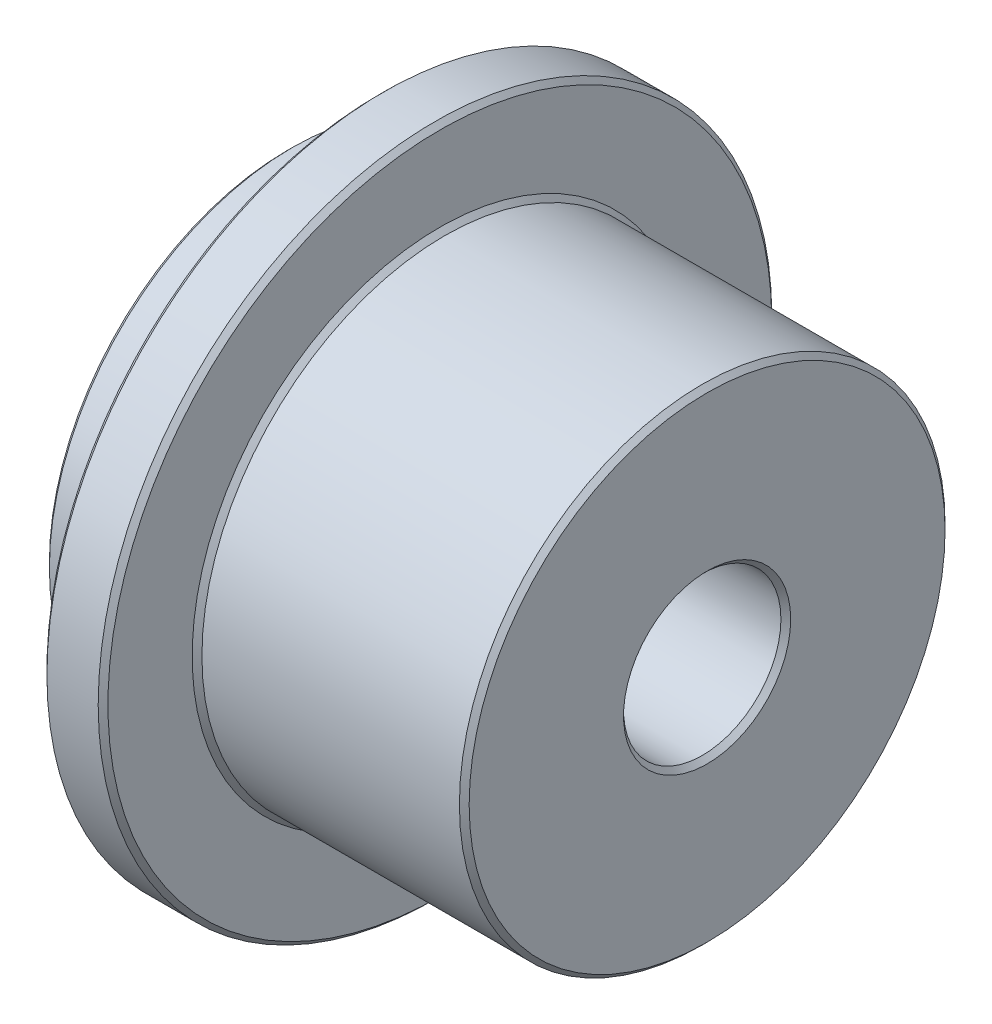
SolidWorks part; units mm, degrees
ref_plane "Front Plane" through (0, 0, 0) normal (0, 0, 1) x (1, 0, 0)
ref_plane "Top Plane" through (0, 0, 0) normal (0, 1, 0) x (1, 0, 0)
ref_plane "Right Plane" through (0, 0, 0) normal (1, 0, 0) x (0, 0, -1)
sketch "Sketch1" plane through (0, 0, 0) normal (1, 0, 0) x (0, 0, -1)
  circle A0 centre (0, 0) radius 12.6365
extrude "Boss-Extrude1" add sketch "Sketch1" along normal blind 21.844 contours A0
ref_plane "Plane1" through (7.9375, 0, 0) normal (1, 0, 0) x (0, 0, -1)
sketch "Sketch2" plane through (7.9375, 0, 0) normal (1, 0, 0) x (0, 0, -1)
  circle A0 centre (0, 0) radius 17.526
extrude "Boss-Extrude2" add sketch "Sketch2" against normal blind 3.175
chamfer "Chamfer1" distance 0.254 angle 45 6 edges at (21.844, 0, -12.6365) (0, 0, -12.6365) (7.9375, 0, -12.6365) (4.7625, 0, -12.6365) (4.7625, 0, -17.526) (7.9375, 0, -17.526)
sketch "Sketch3" plane through (21.844, 0, 0) normal (1, 0, 0) x (0, 0, -1)
  circle A0 centre (0, 0) radius 4.0957
extrude "Cut-Extrude1" cut sketch "Sketch3" against normal through all
chamfer "Chamfer2" distance 0.254 angle 45 2 edges at (0, 0, -4.0957) (21.844, 0, -4.0957)
